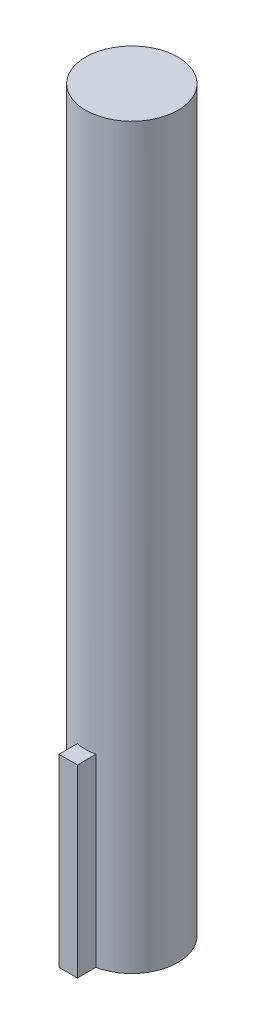
SolidWorks part; units mm, degrees
ref_plane "Front Plane" through (0, 0, 0) normal (0, 0, 1) x (1, 0, 0)
ref_plane "Top Plane" through (0, 0, 0) normal (0, 1, 0) x (1, 0, 0)
ref_plane "Right Plane" through (0, 0, 0) normal (1, 0, 0) x (0, 0, -1)
sketch "Sketch1" plane through (0, 0, 0) normal (0, 1, 0) x (1, 0, 0)
  line L0 (-0.5, -2.4495) -> (-0.5, -3.4495)
  line L1 (-0.5, -3.4495) -> (0.5, -3.4495)
  line L2 (0.5, -3.4495) -> (0.5, -2.4495)
  arc A0 (0.5, -2.4495) -> (-0.5, -2.4495) centre (0, 0) ccw
  dimension "D1" = 5
  dimension "D2" = 1
  dimension "D3" = 1
extrude "Boss-Extrude1" add sketch "Sketch1" along normal blind 10
sketch "Sketch2" plane through (0, 10, 0) normal (0, 1, 0) x (1, 0, 0)
  circle A0 centre (0, 0) radius 2.5
  dimension "D1" = 5
extrude "Boss-Extrude2" add sketch "Sketch2" along normal blind 30
